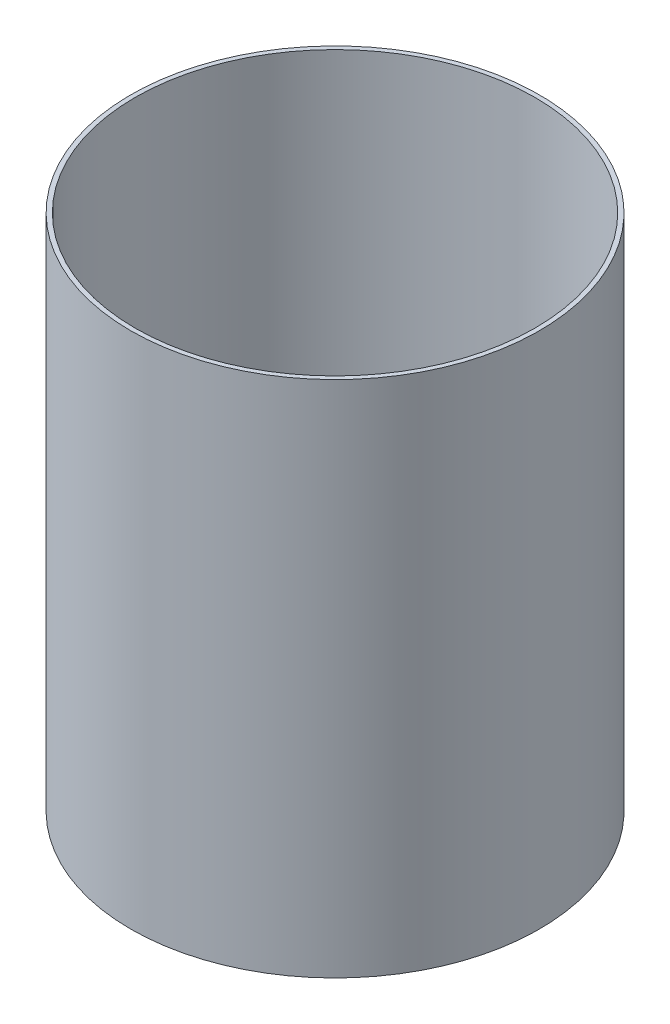
SolidWorks part; units mm, degrees
material "AISI 1035 Steel (SS)"
ref_plane "Front Plane" through (0, 0, 0) normal (0, 0, 1) x (1, 0, 0)
ref_plane "Top Plane" through (0, 0, 0) normal (0, 1, 0) x (1, 0, 0)
ref_plane "Right Plane" through (0, 0, 0) normal (1, 0, 0) x (0, 0, -1)
sketch "Sketch1" plane through (0, 0, 0) normal (0, 1, 0) x (1, 0, 0)
  circle A0 centre (0, 0) radius 690
  dimension "D1" = 1380
extrude "Boss-Extrude1" add sketch "Sketch1" along normal mid plane 1750
sketch "Sketch2" plane through (0, 0, 0) normal (0, 1, 0) x (1, 0, 0)
  circle A0 centre (0, 0) radius 675
  dimension "D1" = 1350
extrude "Cut-Extrude1" cut sketch "Sketch2" against normal through all both and the other way through all
